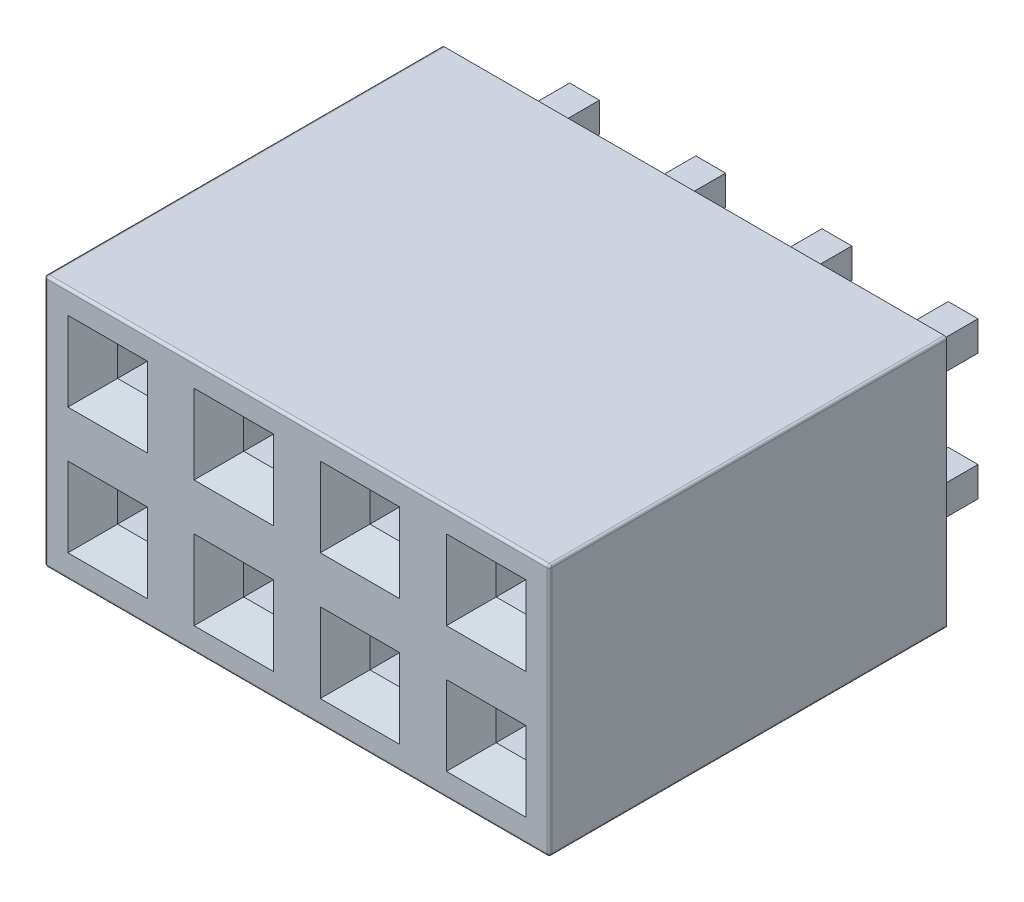
SolidWorks part; units mm, degrees
ref_plane "前视基准面" through (0, 0, 0) normal (0, 0, 1) x (1, 0, 0)
ref_plane "上视基准面" through (0, 0, 0) normal (0, 1, 0) x (1, 0, 0)
ref_plane "右视基准面" through (0, 0, 0) normal (1, 0, 0) x (0, 0, -1)
sketch "草图1" plane through (0, 0, 0) normal (0, 0, 1) x (1, 0, 0)
  line L0 (-1000, 0) -> (49000, 0) construction
  line L1 (0, -1000) -> (0, 49000) construction
  line L2 (-5.08, 2.54) -> (5.08, 2.54)
  line L3 (5.08, 2.54) -> (5.08, -2.54)
  line L4 (-5.08, -2.54) -> (5.08, -2.54)
  line L5 (-5.08, 2.54) -> (-5.08, -2.54)
  point P9 (5.08, 0)
  point P11 (0, -2.54)
  point P12 (0, 2.54)
  dimension "D1" = 10.16
  dimension "D2" = 5.08
extrude "凸台-拉伸1" add sketch "草图1" along normal blind 8
sketch "草图2" plane through (0, 0, 8) normal (0, 0, 1) x (1, 0, 0)
  line L0 (-5.08, 0) -> (5.08, 0) construction
  line L1 (-5.08, 2.54) -> (-5.08, -2.54) construction
  line L2 (5.08, -2.54) -> (5.08, 2.54) construction
  line L3 (0, 2.54) -> (0, -2.54) construction
  line L4 (5.08, 2.54) -> (-5.08, 2.54) construction
  line L5 (-5.08, -2.54) -> (5.08, -2.54) construction
  line L6 (1.57, 0.97) -> (0.97, 0.97)
  line L7 (-0.97, 1.57) -> (-1.57, 1.57)
  line L8 (-0.97, 1.57) -> (-0.97, 0.97)
  line L9 (-0.97, 0.97) -> (-1.57, 0.97)
  line L10 (-1.57, 1.57) -> (-1.57, 0.97)
  line L11 (0.97, 1.57) -> (0.97, 0.97)
  line L12 (1.57, 1.57) -> (0.97, 1.57)
  line L13 (1.57, 1.57) -> (1.57, 0.97)
  line L14 (4.11, 0.97) -> (3.51, 0.97)
  line L15 (3.51, 1.57) -> (3.51, 0.97)
  line L16 (4.11, 1.57) -> (3.51, 1.57)
  line L17 (4.11, 1.57) -> (4.11, 0.97)
  line L18 (-0.97, -1.57) -> (-1.57, -1.57)
  line L19 (-1.57, -0.97) -> (-1.57, -1.57)
  line L20 (-0.97, -0.97) -> (-1.57, -0.97)
  line L21 (-0.97, -0.97) -> (-0.97, -1.57)
  line L22 (1.57, -1.57) -> (0.97, -1.57)
  line L23 (0.97, -0.97) -> (0.97, -1.57)
  line L24 (1.57, -0.97) -> (0.97, -0.97)
  line L25 (1.57, -0.97) -> (1.57, -1.57)
  line L26 (4.11, -1.57) -> (3.51, -1.57)
  line L27 (3.51, -0.97) -> (3.51, -1.57)
  line L28 (4.11, -0.97) -> (3.51, -0.97)
  line L29 (4.11, -0.97) -> (4.11, -1.57)
  line L30 (-4.11, -0.97) -> (-4.11, -1.57)
  line L31 (-4.11, -0.97) -> (-3.51, -0.97)
  line L32 (-3.51, -0.97) -> (-3.51, -1.57)
  line L33 (-4.11, -1.57) -> (-3.51, -1.57)
  line L34 (-4.11, 1.57) -> (-4.11, 0.97)
  line L35 (-4.11, 1.57) -> (-3.51, 1.57)
  line L36 (-3.51, 1.57) -> (-3.51, 0.97)
  line L37 (-4.11, 0.97) -> (-3.51, 0.97)
  circle A0 centre (-1.27, 1.27) radius 0.3 construction
  dimension "D1" = 0.6
  dimension "D2" = 2.54
  dimension "D3" = 2.54
extrude "切除-拉伸1" cut sketch "草图2" against normal blind 5
sketch "草图3" plane through (0, 0, 0) normal (0, 0, -1) x (-1, 0, 0)
  line L0 (4.11, -1.57) -> (3.51, -1.57)
  line L1 (3.51, -1.57) -> (3.51, -0.97)
  line L2 (3.51, -0.97) -> (4.11, -0.97)
  line L3 (4.11, -0.97) -> (4.11, -1.57)
extrude "凸台-拉伸2" add sketch "草图3" along normal blind 1.6 separate body
pattern_linear "阵列(线性)1" count 4 spacing 2.54 along (1, 0, 0) count 2 spacing 2.54 along (0, 1, 0) of "凸台-拉伸2"
chamfer "倒角1" distance 0.5 angle 45 4 edges at (3.51, -1.27, 8) (3.81, -1.57, 8) (4.11, -1.27, 8) (3.81, -0.97, 8)
chamfer "倒角2" distance 0.5 angle 45 28 edges at (3.81, 1.57, 8) (4.11, 1.27, 8) (3.81, 0.97, 8) (3.51, 1.27, 8) (1.57, 1.27, 8) (1.27, 1.57, 8) (0.97, 1.27, 8) (1.27, 0.97, 8) (-0.97, 1.27, 8) (-1.27, 1.57, 8) (-1.27, 0.97, 8) (-1.57, 1.27, 8) (-3.51, 1.27, 8) (-3.81, 1.57, 8) (-3.81, 0.97, 8) (-4.11, 1.27, 8) (-4.11, -1.27, 8) (-3.81, -1.57, 8) (-3.51, -1.27, 8) (-3.81, -0.97, 8) (-0.97, -1.27, 8) (-1.27, -1.57, 8) (-1.57, -1.27, 8) (-1.27, -0.97, 8) (0.97, -1.27, 8) (1.27, -0.97, 8) (1.27, -1.57, 8) (1.57, -1.27, 8)
fillet "圆角1" radius 0.05 8 edges at (-5.08, -2.54, 4) (-5.08, 0, 8) (0, -2.54, 8) (-5.08, 2.54, 4) (0, 2.54, 8) (5.08, 0, 8) (5.08, -2.54, 4) (5.08, 2.54, 4)
